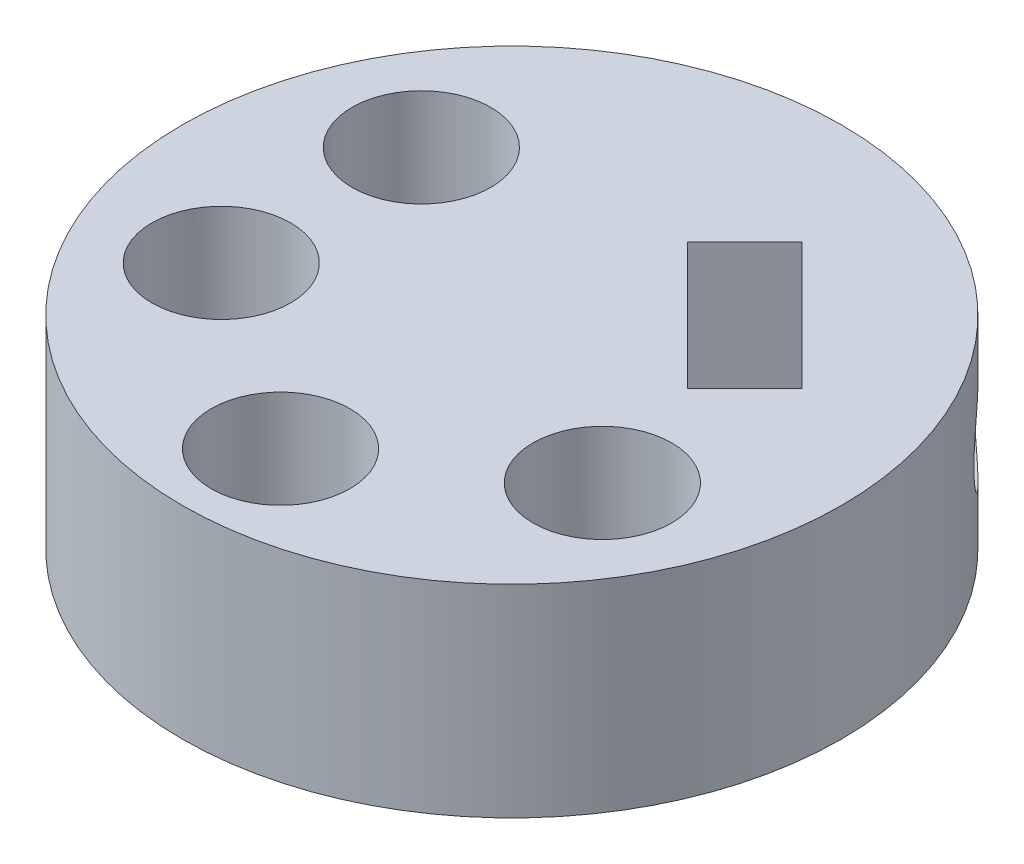
SolidWorks part; units mm, degrees
material "ABS"
ref_plane "Plano frontal" through (0, 0, 0) normal (0, 0, 1) x (1, 0, 0)
ref_plane "Plano superior" through (0, 0, 0) normal (0, 1, 0) x (1, 0, 0)
ref_plane "Plano direito" through (0, 0, 0) normal (1, 0, 0) x (0, 0, -1)
sketch "Esboço1" plane through (0, 0, 0) normal (0, 1, 0) x (1, 0, 0)
  circle A4 centre (-6.59, 3.46) radius 2.4
  circle A6 centre (6.59, -3.46) radius 2.4
  circle A8 centre (0, -8) radius 2.4
  circle A9 centre (-6.59, -3.46) radius 2.4
sketch "Esboço2" plane through (0, 0, 0) normal (0, 1, 0) x (1, 0, 0)
  circle A0 centre (0, 0) radius 11.4
extrude "Ressalto-extrusão3" add sketch "Esboço2" along normal blind 7
extrude "Corte-extrusão4" cut sketch "Esboço1" along normal blind 15
sketch "Esboço3" plane through (0, 7, 0) normal (0, 1, 0) x (1, 0, 0)
  line L2 (0.8, 0.8) -> (0.8, 2.2627)
  line L3 (-0.8, 0.8) -> (-0.8, 2.2627)
  line L4 (-0.8, 2.2627) -> (-0.8, 0.8)
  line L5 (0.8, -0.8) -> (0.8, -2.2627)
  line L8 (0.8, 0.8) -> (2.2627, 0.8)
  line L9 (2.2627, 0.8) -> (0.8, 0.8)
  line L10 (0.8, -0.8) -> (2.2627, -0.8)
  line L11 (2.2627, -0.8) -> (0.8, -0.8)
  line L12 (-0.8, -0.8) -> (-2.2627, -0.8)
  line L13 (-0.8, 0.8) -> (-2.2627, 0.8)
  line L14 (-0.8, -0.8) -> (-0.8, -2.2627)
  arc A0 (0.8, 2.2627) -> (-0.8, 2.2627) centre (0, 0) ccw
  arc A1 (-2.2627, 0.8) -> (-2.2627, -0.8) centre (0, 0) ccw
  arc A2 (-0.8, -2.2627) -> (0.8, -2.2627) centre (0, 0) ccw
  arc A3 (2.2627, -0.8) -> (2.2627, 0.8) centre (0, 0) ccw
extrude "Ressalto-extrusão4" [suppressed] add sketch "Esboço3" along normal blind 9 contours L10 A3 L8 L2 A0 L3 L13 A1 L12 L14 A2 L5
sketch "Esboço4" plane through (0, 0, 0) normal (0, -1, 0) x (-1, 0, 0)
  circle A1 centre (0, 0) radius 2
sketch "Esboço6" plane through (0, 0, 0) normal (0, -1, 0) x (1, 0, 0)
  circle A0 centre (0, 0) radius 3.9
extrude "Ressalto-extrusão5" add sketch "Esboço6" along normal blind 2
extrude "Corte-extrusão7" cut sketch "Esboço4" against normal blind 6 and the other way blind 4
sketch "Esboço7" plane through (0, 0, 0) normal (0, -1, 0) x (1, 0, 0)
  line L0 (0, 0) -> (3.0406, -3.0406)
  line L1 (3.0406, -3.0406) -> (5.2326, -0.8485)
  line L2 (3.0406, -3.0406) -> (0.8485, -5.2326)
  line L3 (0.8485, -5.2326) -> (2.8284, -7.2125)
  line L4 (5.2326, -0.8485) -> (7.2125, -2.8284)
  line L5 (7.2125, -2.8284) -> (2.8284, -7.2125)
extrude "Corte-extrusão8" cut sketch "Esboço7" against normal blind 10.5 contours L5 L4 L1 L2 L3
sketch "Esboço8" plane through (3.0406, 0, -3.0406) normal (0.7071, 0, -0.7071) x (-0.7071, 0, -0.7071)
  line L0 (3.1, 0) -> (-3.1, 0) construction
  circle A0 centre (0, 3.5) radius 1.5
  dimension "D1" = 3.5
extrude "Corte-extrusão9" cut sketch "Esboço8" against normal up to next and the other way through all
